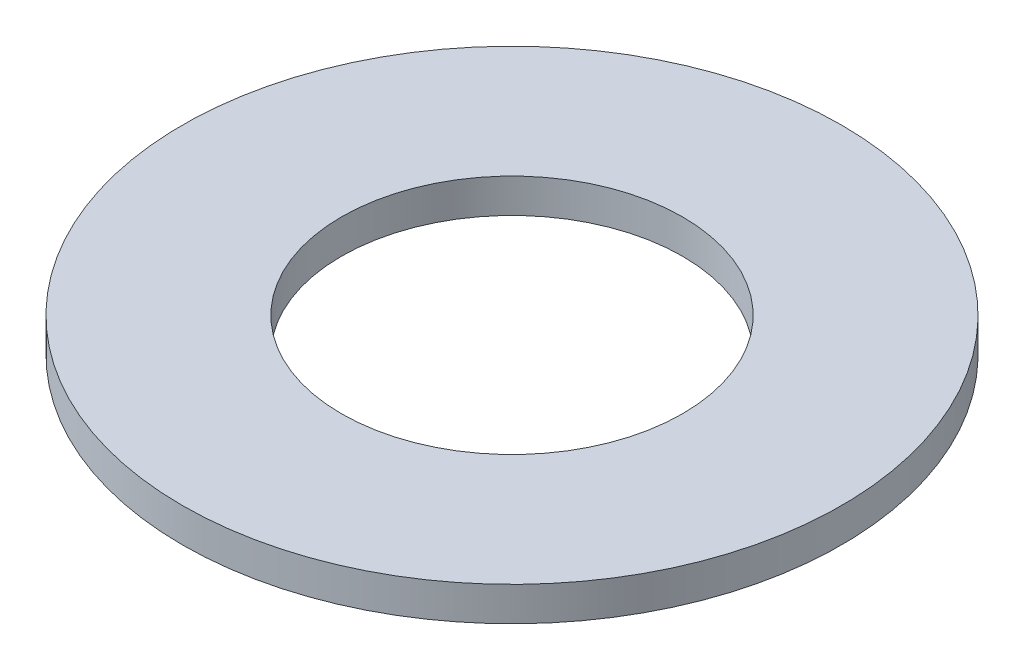
SolidWorks part; units mm, degrees
ref_plane "Front Plane" through (0, 0, 0) normal (0, 0, 1) x (1, 0, 0)
ref_plane "Top Plane" through (0, 0, 0) normal (0, 1, 0) x (1, 0, 0)
ref_plane "Right Plane" through (0, 0, 0) normal (1, 0, 0) x (0, 0, -1)
sketch "Sketch1" plane through (0, 0, 0) normal (0, 1, 0) x (1, 0, 0)
  circle A0 centre (0, 0) radius 22.21
  circle A2 centre (0, 0) radius 11.4935
  dimension "D1" = 44.42
  dimension "D2" = 22.987
extrude "Boss-Extrude1" add sketch "Sketch1" along normal blind 2.3
equation "\"can_outer_diameter\"= 44.42mm"
equation "\"D1@Sketch1\"=\"can_outer_diameter\""
equation "\"can_thickness\"= 2.3"
equation "\"can_height\"=104.902"
equation "\"neck_diameter\"=22.987"
equation "\"D2@Sketch1\"=\"neck_diameter\""
equation "\"D1@Boss-Extrude1\"=\"can_thickness\""
